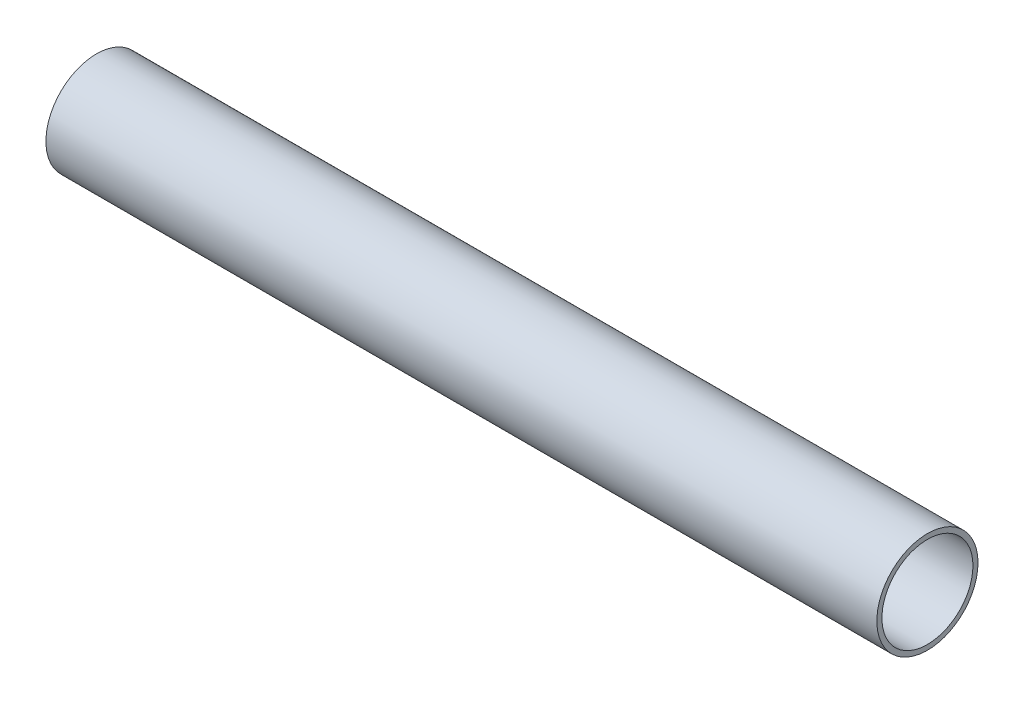
SolidWorks part; units mm, degrees
material "PC High Viscosity"
ref_plane "Front Plane" through (0, 0, 0) normal (0, 0, 1) x (1, 0, 0)
ref_plane "Top Plane" through (0, 0, 0) normal (0, 1, 0) x (1, 0, 0)
ref_plane "Right Plane" through (0, 0, 0) normal (1, 0, 0) x (0, 0, -1)
sketch "Sketch1" plane through (0, 0, 0) normal (1, 0, 0) x (0, 0, -1)
  circle A0 centre (0, 0) radius 15.875
  dimension "D1" = 31.75
extrude "Extrude-Thin1" add sketch "Sketch1" along normal mid plane 260.8 thin thin type one direction reverse wall 1.5875
